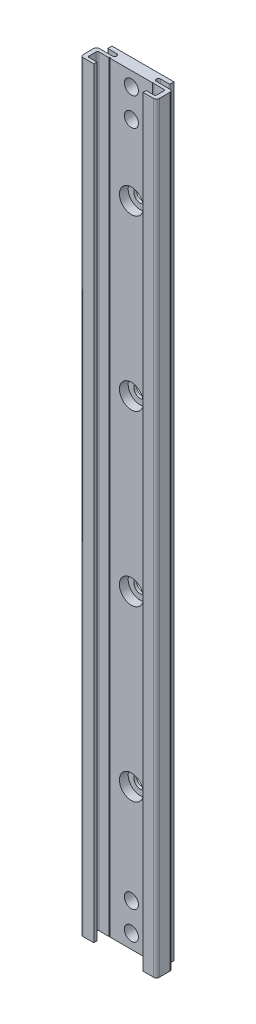
SolidWorks part; units mm, degrees
ref_plane "Front Plane" through (0, 0, 0) normal (0, 0, 1) x (1, 0, 0)
ref_plane "Top Plane" through (0, 0, 0) normal (0, 1, 0) x (1, 0, 0)
ref_plane "Right Plane" through (0, 0, 0) normal (1, 0, 0) x (0, 0, -1)
ref_plane "Plane1" through (0, 300, 0) normal (0, 1, 0) x (1, 0, 0)
sketch "Sketch1" plane through (0, 300, 0) normal (0, 1, 0) x (1, 0, 0)
  line L0 (-13.5, -3) -> (-13.5, -8.7)
  line L1 (-13.5, -8.7) -> (13.5, -8.7)
  line L2 (13.5, -8.7) -> (13.5, -3)
  line L3 (13.5, -3) -> (7.8, -3)
  line L4 (7.8, -1.5) -> (11, -1.5)
  line L5 (11, -1.5) -> (11, 0)
  line L6 (11, 0) -> (-11, 0)
  line L7 (-11, 0) -> (-11, -1.5)
  line L8 (-11, -1.5) -> (-7.8, -1.5)
  line L9 (-7.8, -3) -> (-13.5, -3)
  arc A0 (7.8, -3) -> (7.8, -1.5) centre (7.8, -2.25) cw
  arc A1 (-7.8, -1.5) -> (-7.8, -3) centre (-7.8, -2.25) cw
extrude "Boss-Extrude1" add sketch "Sketch1" against normal blind 270
sketch "Sketch2" plane through (0, 30, 0) normal (0, -1, 0) x (1, 0, 0)
  line L0 (8.75, 8.7) -> (-8.75, 8.7)
  line L1 (-8.75, 8.7) -> (-8.75, 7.6)
  line L2 (-8.75, 7.6) -> (-12, 7.6)
  line L3 (-12, 7.6) -> (-12, 4.1)
  line L4 (-12, 4.1) -> (12, 4.1)
  line L5 (12, 4.1) -> (12, 7.6)
  line L6 (12, 7.6) -> (8.75, 7.6)
  line L7 (8.75, 7.6) -> (8.75, 8.7)
extrude "Cut-Extrude1" cut sketch "Sketch2" against normal through all
hole_wizard "Ø0.4 (0.4) Diameter Hole1" positions "Sketch4" profile "Sketch3" hole size "Ø0.4" standard "ANSI Metric"
sketch "Sketch4" plane through (0, 300, 0) normal (0, 1, 0) x (1, 0, 0)
  point P0 (-7.75, -4.1)
  point P1 (7.75, -4.1)
sketch "Sketch3" plane through (-7.75, 300, 4.1) normal (1, 0, 0) x (0, 0, 1)
  line L0 (0, 0) -> (0, 270)
  line L1 (0, 270) -> (0.2, 270)
  line L2 (0.2, 270) -> (0.2, 0)
  line L5 (0.2, 0) -> (0, 0)
  line L11 (0, -6.35) -> (0, 107.95) construction
  dimension "Thru Hole Dia." = 0.4
  dimension "Thru Hole Depth" = 270
hole_wizard "CBORE for M4 Hex Head Machine Screw1" positions "Sketch6" profile "Sketch5" counterbore size "M4" standard "ANSI Metric"
sketch "Sketch6" plane through (0, 0, 4.1) normal (0, 0, 1) x (1, 0, 0)
  point P0 (0, 260)
  point P1 (0, 200)
  point P2 (0, 140)
  point P3 (0, 80)
  point P4 (0, 20)
sketch "Sketch5" plane through (0, 260, 4.1) normal (1, 0, 0) x (0, -1, 0)
  line L0 (0, 0) -> (0, 4.1)
  line L1 (0, 4.1) -> (2.25, 4.1)
  line L3 (2.25, 4.1) -> (2.25, 3.1)
  line L4 (2.25, 3.1) -> (4.25, 3.1)
  line L5 (4.25, 3.1) -> (4.25, 0)
  line L7 (4.25, 0) -> (0, 0)
  line L11 (0, -6.35) -> (0, 107.95) construction
  dimension "Thru Hole Dia." = 4.5
  dimension "Thru Hole Depth" = 4.1
  dimension "C'Bore Dia." = 8.5
  dimension "C'Bore Depth" = 3.1
fillet "Fillet1" radius 0.2 2 edges at (11, 165, 1.5) (-11, 165, 1.5)
fillet "Fillet2" radius 0.5 4 edges at (12, 165, 4.1) (-12, 165, 7.6) (12, 165, 7.6) (-12, 165, 4.1)
fillet "Fillet3" radius 1 4 edges at (-13.5, 165, 8.7) (-13.5, 165, 3) (13.5, 165, 3) (13.5, 165, 8.7)
sketch "Sketch7" plane through (0, 0, 4.1) normal (0, 0, 1) x (1, 0, 0)
  line L0 (0, 300) -> (0, 30) construction
  line L1 (-7.55, 300) -> (7.55, 300) construction
  line L2 (-7.55, 30) -> (7.55, 30) construction
  circle A0 centre (0, 285) radius 2.5
  circle A1 centre (0, 45) radius 2.5
  circle A2 centre (0, 35) radius 2.5
  circle A3 centre (0, 295) radius 2.5
  dimension "D1" = 5
  dimension "D2" = 5
  dimension "D3" = 5
  dimension "D4" = 5
  dimension "D5" = 15
  dimension "D6" = 10
  dimension "D7" = 15
  dimension "D8" = 10
extrude "Cut-Extrude2" cut sketch "Sketch7" against normal up to next
